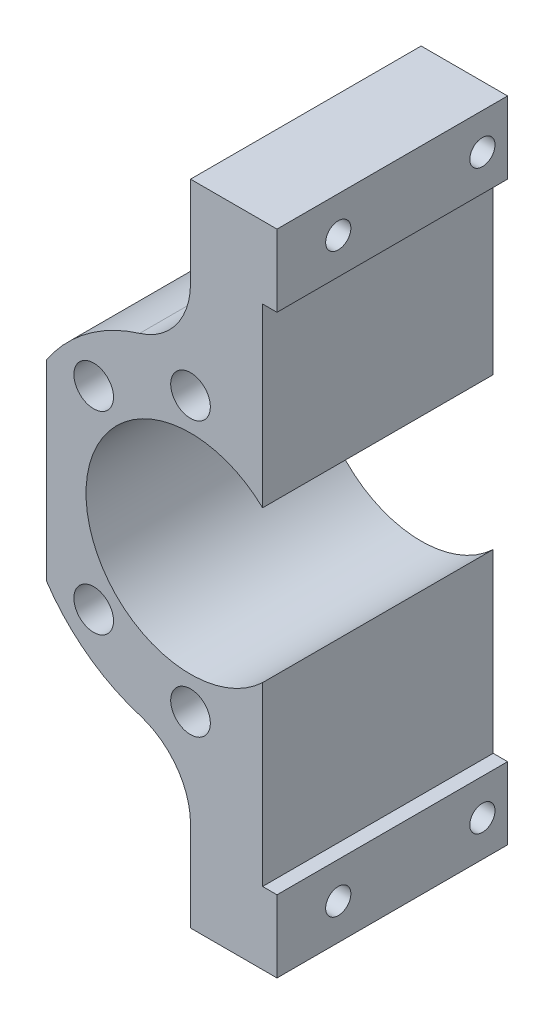
SolidWorks part; units mm, degrees
ref_plane "Plan de face" through (0, 0, 0) normal (0, 0, 1) x (1, 0, 0)
ref_plane "Plan de dessus" through (0, 0, 0) normal (0, 1, 0) x (1, 0, 0)
ref_plane "Plan de droite" through (0, 0, 0) normal (1, 0, 0) x (0, 0, -1)
sketch "Esquisse2" plane through (0, 0, 0) normal (0, 0, 1) x (1, 0, 0)
  line L1 (-22.3865, 12.0572) -> (-22.3865, -14.4758)
  line L2 (-2.3865, 22.7907) -> (7.6135, 22.7907)
  line L5 (7.6135, -25.2093) -> (-2.3865, -25.2093)
  line L6 (7.6135, -11.7093) -> (7.6135, -25.2093)
  line L7 (7.6135, 9.2907) -> (7.6135, 22.7907)
  arc A0 (7.6135, -11.7093) -> (7.6135, 9.2907) centre (-2.3865, -1.2093) cw
  arc A2 (-22.3865, 12.0572) -> (-2.3865, 22.7907) centre (-2.3865, -1.2093) cw
  arc A3 (-22.3865, -14.4758) -> (-2.3865, -25.2093) centre (-2.3865, -1.2093) ccw
  circle A4 centre (-2.3865, -1.2093) radius 19 construction
  circle A5 centre (-2.3865, 17.7907) radius 2.75
  circle A6 centre (-15.8215, 12.2258) radius 2.75
  circle A8 centre (-2.3865, -20.2093) radius 2.75
  circle A10 centre (-15.8215, -14.6443) radius 2.75
  dimension "D2" = 24
  dimension "D3" = 38
  dimension "D4" = 5.5
  dimension "D5" = 30
  dimension "D9" = 14.5
  dimension "D1" = 26.533
  dimension "D6" = 45
  dimension "D8" = 45
extrude "Boss.-Extru.1" add sketch "Esquisse2" along normal blind 32
sketch "Esquisse3" plane through (7.6135, 0, 0) normal (1, 0, 0) x (0, 0, -1)
  line L1 (0, 22.7907) -> (-32, 22.7907)
  line L2 (-32, 22.7907) -> (-32, 43.7907)
  line L3 (-32, 43.7907) -> (0, 43.7907)
  line L4 (0, 43.7907) -> (0, 22.7907)
  line L5 (0, -25.2093) -> (0, -11.7093) construction
  line L6 (-32, -25.2093) -> (0, -25.2093)
  line L7 (-32, -25.2093) -> (-32, -46.2093)
  line L8 (-32, -46.2093) -> (0, -46.2093)
  line L9 (0, -25.2093) -> (0, -46.2093)
  line L10 (-32, 22.7907) -> (-32, -25.2093) construction
  line L11 (-23.5, 38.7907) -> (-23.5, -41.2093) construction
  circle A0 centre (-23.5, 38.7907) radius 1.75
  circle A1 centre (-3.5, 38.7907) radius 1.75
  circle A2 centre (-23.5, -41.2093) radius 1.75
  circle A3 centre (-3.5, -41.2093) radius 1.75
  point P21 (-23.5, -1.2093)
  point P22 (-32, -1.2093)
  dimension "D1" = 3.5
  dimension "D2" = 20
  dimension "D3" = 80
  dimension "D4" = 5
  dimension "D5" = 3.5
extrude "Boss.-Extru.2" add sketch "Esquisse3" against normal up to vertex (10 mm away)
sketch "Esquisse4" plane through (7.6135, 0, 0) normal (1, 0, 0) x (0, 0, -1)
  line L0 (0, 9.2907) -> (0, 43.7907) construction
  line L1 (-32, 43.7907) -> (0, 43.7907)
  line L2 (-32, 43.7907) -> (-32, 33.7907)
  line L3 (-32, 33.7907) -> (0, 33.7907)
  line L4 (0, 43.7907) -> (0, 33.7907)
  line L5 (0, -46.2093) -> (0, -11.7093) construction
  line L6 (-32, -46.2093) -> (0, -46.2093)
  line L7 (-32, -46.2093) -> (-32, -36.2093)
  line L8 (-32, -36.2093) -> (0, -36.2093)
  line L9 (0, -46.2093) -> (0, -36.2093)
  circle A0 centre (-3.5, -41.2093) radius 1.75 construction
  circle A1 centre (-23.5, -41.2093) radius 1.75 construction
  circle A2 centre (-3.5, 38.7907) radius 1.75 construction
  circle A3 centre (-23.5, 38.7907) radius 1.75 construction
  circle A4 centre (-3.5, -41.2093) radius 1.75
  circle A5 centre (-23.5, -41.2093) radius 1.75
  circle A6 centre (-3.5, 38.7907) radius 1.75
  circle A7 centre (-23.5, 38.7907) radius 1.75
  dimension "D1" = 10
extrude "Boss.-Extru.3" add sketch "Esquisse4" along normal blind 2
fillet "Congé1" radius 10 2 edges at (-2.3865, -25.2093, 16) (-2.3865, 22.7907, 16)
